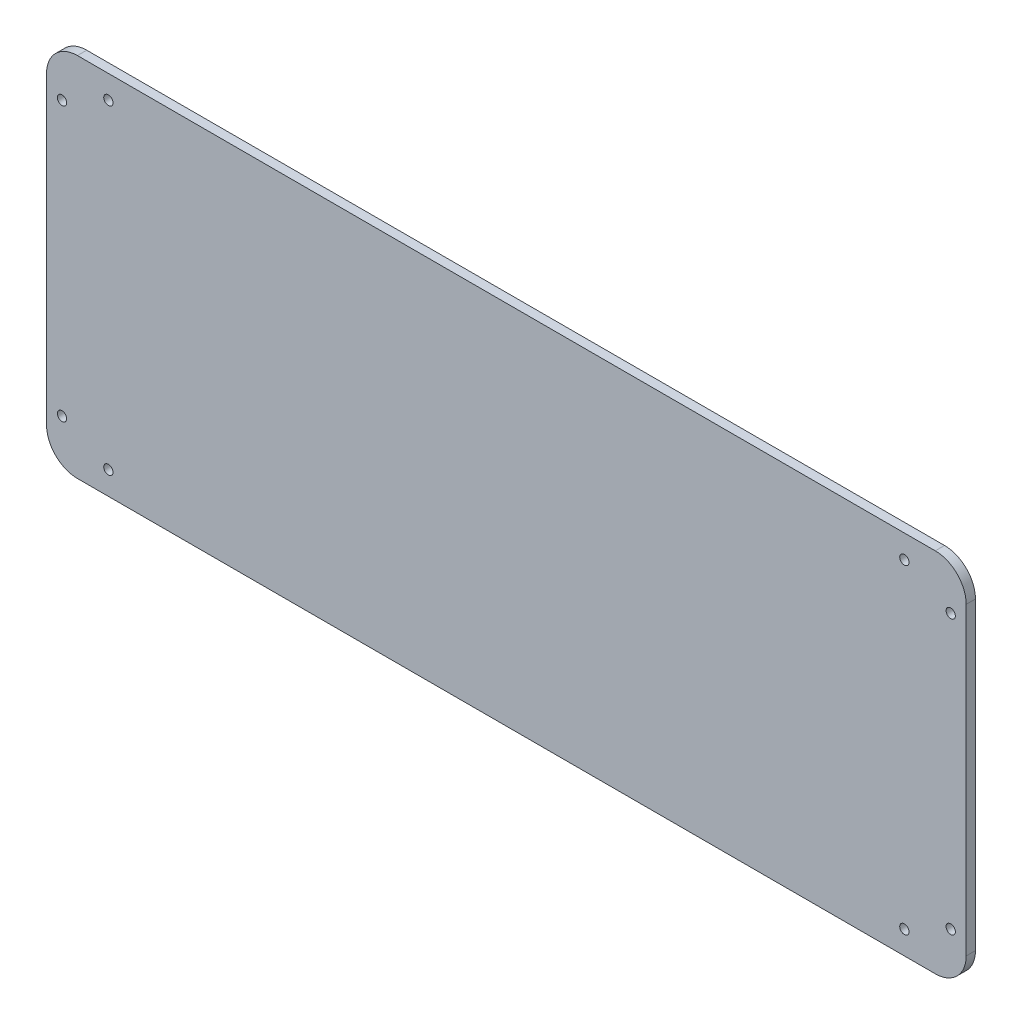
SolidWorks part; units mm, degrees
ref_plane "Front Plane" through (0, 0, 0) normal (0, 0, 1) x (1, 0, 0)
ref_plane "Top Plane" through (0, 0, 0) normal (0, 1, 0) x (1, 0, 0)
ref_plane "Right Plane" through (0, 0, 0) normal (1, 0, 0) x (0, 0, -1)
sketch "Sketch1" plane through (0, 0, 0) normal (0, 0, 1) x (1, 0, 0)
  line L1 (0, 0) -> (297.5, 0)
  line L2 (0, 0) -> (0, 118.5)
  line L3 (0, 118.5) -> (297.5, 118.5)
  line L4 (297.5, 0) -> (297.5, 118.5)
  dimension "D1" = 297.5
  dimension "D2" = 118.5
extrude "Boss-Extrude1" add sketch "Sketch1" along normal blind 3
sketch "Sketch2" plane through (0, 0, 3) normal (0, 0, 1) x (1, 0, 0)
  circle A0 centre (5, 15) radius 1.5 construction
  circle A1 centre (20, 7.5) radius 1.5 construction
  circle A2 centre (20, 111) radius 1.5 construction
  circle A3 centre (5, 103.5) radius 1.5 construction
  circle A4 centre (292.5, 15) radius 1.5 construction
  circle A5 centre (277.5, 7.5) radius 1.5 construction
  circle A6 centre (292.5, 103.5) radius 1.5 construction
  circle A7 centre (277.5, 111) radius 1.5 construction
  circle A8 centre (5, 15) radius 1.5
  circle A9 centre (20, 7.5) radius 1.5
  circle A10 centre (20, 111) radius 1.5
  circle A11 centre (5, 103.5) radius 1.5
  circle A12 centre (292.5, 15) radius 1.5
  circle A13 centre (277.5, 7.5) radius 1.5
  circle A14 centre (292.5, 103.5) radius 1.5
  circle A15 centre (277.5, 111) radius 1.5
extrude "Cut-Extrude1" cut sketch "Sketch2" against normal blind 3
fillet "Fillet1" radius 10 4 edges at (297.5, 118.5, 1.5) (297.5, 0, 1.5) (0, 0, 1.5) (0, 118.5, 1.5)
